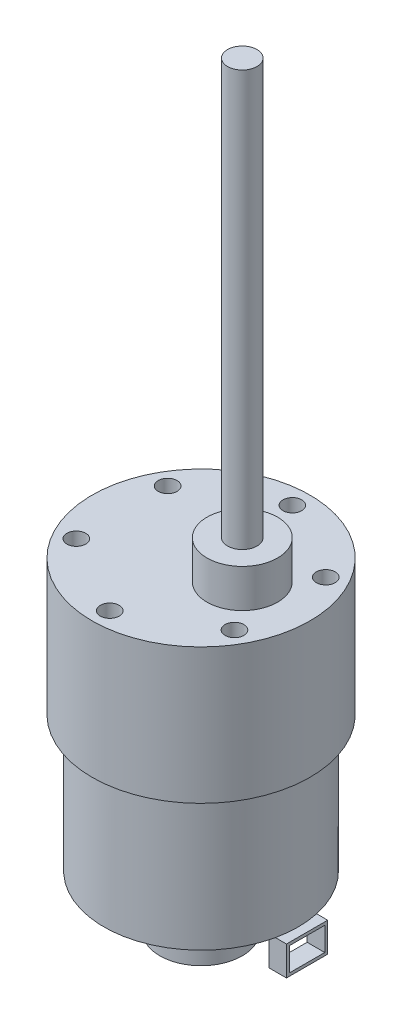
SolidWorks part; units mm, degrees
ref_plane "前视基准面" through (0, 0, 0) normal (0, 0, 1) x (1, 0, 0)
ref_plane "上视基准面" through (0, 0, 0) normal (0, 1, 0) x (1, 0, 0)
ref_plane "右视基准面" through (0, 0, 0) normal (1, 0, 0) x (0, 0, -1)
sketch "草图1" plane through (0, 0, 0) normal (0, 1, 0) x (1, 0, 0)
  circle A0 centre (0, 0) radius 16.5
extrude "凸台-拉伸1" add sketch "草图1" along normal blind 46
sketch "草图2" plane through (0, 0, 0) normal (0, -1, 0) x (1, 0, 0)
  circle A0 centre (0, 0) radius 7
extrude "凸台-拉伸2" add sketch "草图2" along normal blind 9
sketch "草图3" plane through (0, 0, 0) normal (0, -1, 0) x (1, 0, 0)
  line L1 (15, -3.5) -> (18, -3.5)
  line L2 (15, -3.5) -> (15, 3.5)
  line L3 (15, 3.5) -> (18, 3.5)
  line L4 (18, -3.5) -> (18, 3.5)
  line L5 (15, -3.5) -> (18, 3.5) construction
  line L6 (15, 3.5) -> (18, -3.5) construction
  circle A0 centre (0, 0) radius 16.5 construction
  point P0 (16.5, 0)
extrude "凸台-拉伸3" add sketch "草图3" along normal blind 5
sketch "草图4" plane through (18, 0, 0) normal (1, 0, 0) x (0, 0, -1)
  line L1 (3, -4.5) -> (-3, -4.5)
  line L2 (3, -4.5) -> (3, -0.5)
  line L3 (3, -0.5) -> (-3, -0.5)
  line L4 (-3, -4.5) -> (-3, -0.5)
  line L5 (3, -4.5) -> (-3, -0.5) construction
  line L6 (3, -0.5) -> (-3, -4.5) construction
  point P0 (0, -2.5)
extrude "切除-拉伸1" cut sketch "草图4" against normal blind 3
sketch "草图5" plane through (0, 46, 0) normal (0, 1, 0) x (1, 0, 0)
  circle A0 centre (7, 0) radius 6
extrude "凸台-拉伸4" add sketch "草图5" along normal blind 6.5
sketch "草图7" plane through (0, 52.5, 0) normal (0, 1, 0) x (1, 0, 0)
  circle A0 centre (7, 0) radius 2.5
extrude "凸台-拉伸5" add sketch "草图7" along normal blind 70.5
sketch "草图8" plane through (0, 46, 0) normal (0, 1, 0) x (1, 0, 0)
  circle A0 centre (0, 0) radius 18.5
  circle A1 centre (0, 0) radius 16.5
extrude "凸台-拉伸6" add sketch "草图8" against normal blind 23
sketch "草图9" plane through (0, 46, 0) normal (0, 1, 0) x (1, 0, 0)
  arc A0 (-14.1508, 6.3249) -> (-14.1508, -6.3249) centre (0, 0) ccw
  arc A1 (-1.5979, 15.4174) -> (-12.5529, 9.0925) centre (0, 0) ccw
  circle A2 centre (0, 15.5) radius 1.6
  circle A3 centre (13.4234, 7.75) radius 1.6
  circle A4 centre (13.4234, -7.75) radius 1.6
  circle A5 centre (0, -15.5) radius 1.6
  circle A6 centre (-13.4234, -7.75) radius 1.6
  circle A7 centre (-13.4234, 7.75) radius 1.6
  arc A8 (12.5529, 9.0925) -> (1.5979, 15.4174) centre (0, 0) ccw
  arc A9 (14.1508, -6.3249) -> (14.1508, 6.3249) centre (0, 0) ccw
  arc A10 (1.5979, -15.4174) -> (12.5529, -9.0925) centre (0, 0) ccw
  arc A11 (-12.5529, -9.0925) -> (-1.5979, -15.4174) centre (0, 0) ccw
extrude "切除-拉伸2" cut sketch "草图9" against normal blind 10 contours A7 | A2 | A3 | A4 | A5 | A6
